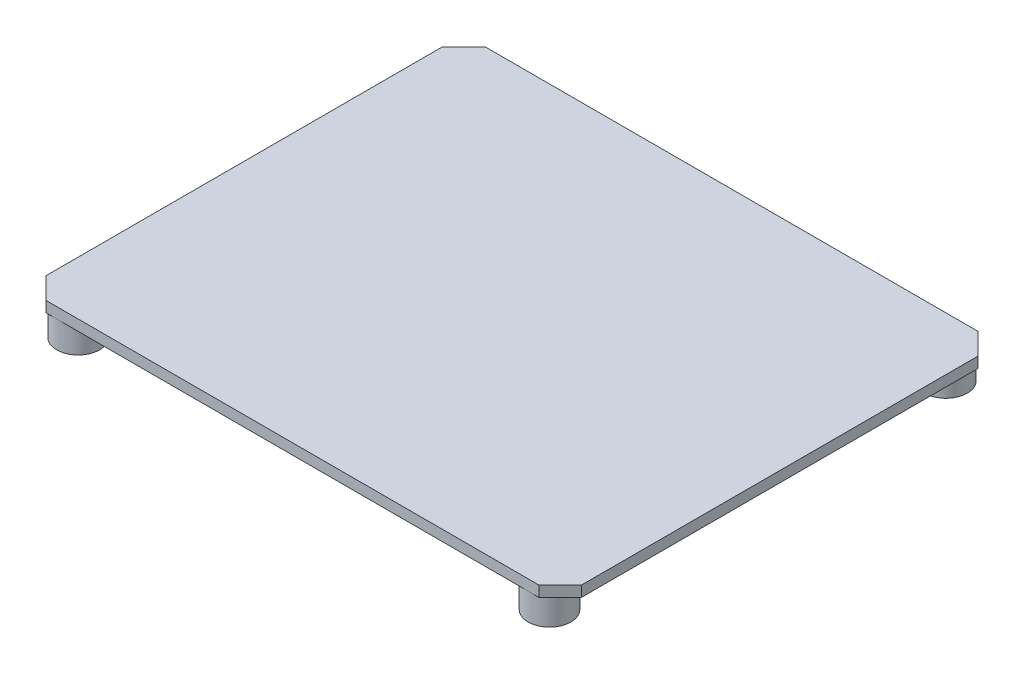
SolidWorks part; units mm, degrees
ref_plane "Front Plane" through (0, 0, 0) normal (0, 0, 1) x (1, 0, 0)
ref_plane "Top Plane" through (0, 0, 0) normal (0, 1, 0) x (1, 0, 0)
ref_plane "Right Plane" through (0, 0, 0) normal (1, 0, 0) x (0, 0, -1)
ref_plane "PZ35_4" through (0, 35.4, 0) normal (0, 1, 0) x (1, 0, 0)
sketch "Sketch1" plane through (0, 35.4, 0) normal (0, 1, 0) x (1, 0, 0)
  line L0 (-46, -102) -> (46, -102)
  line L1 (46, -102) -> (50, -98)
  line L2 (50, -98) -> (50, -24)
  line L3 (50, -24) -> (46, -20)
  line L4 (46, -20) -> (-46, -20)
  line L5 (-46, -20) -> (-50, -24)
  line L6 (-50, -24) -> (-50, -98)
  line L7 (-50, -98) -> (-46, -102)
extrude "Shade Plate" add sketch "Sketch1" along normal blind 2
ref_plane "PZ30_4" through (0, 30.4, 0) normal (0, 1, 0) x (1, 0, 0)
sketch "Sketch2" plane through (0, 30.4, 0) normal (0, 1, 0) x (1, 0, 0)
  circle A0 centre (-44, -24) radius 4
  circle A1 centre (-44, -98) radius 4
  circle A2 centre (44, -24) radius 4
  circle A3 centre (44, -98) radius 4
extrude "Posts" add sketch "Sketch2" along normal blind 5.1
ref_plane "PZ29_9" through (0, 29.9, 0) normal (0, 1, 0) x (1, 0, 0)
sketch "Sketch3" plane through (0, 29.9, 0) normal (0, 1, 0) x (1, 0, 0)
  circle A0 centre (-44, -24) radius 1.25
  circle A1 centre (-44, -98) radius 1.25
  circle A2 centre (44, -24) radius 1.25
  circle A3 centre (44, -98) radius 1.25
extrude "Post Pilots" cut sketch "Sketch3" along normal blind 6.5
equation "\"BOARD_REAR\" = 86.0"
equation "\"BOARD_FRONT\" = 41.0"
equation "\"BOARD_END\" = 22.0"
equation "\"BOARD_ANGLED\" = 30.0"
equation "\"BOARD_DEPTH\" = 41.8431"
equation "\"PCB_T\" = 1.6"
equation "\"ABOVE_PCB\" = 14.0"
equation "\"BELOW_PCB\" = 6.0"
equation "\"MID_PARTS_H\" = 9.0"
equation "\"BOARD_HOLE_PILOT\" = 1.6"
equation "\"J2_X\" = 19.0"
equation "\"DUPONT_DROP\" = 14.0"
equation "\"BEND_R\" = 5.0"
equation "\"BOARD_GAP\" = 3.0"
equation "\"TOF_FOV\" = 25.0"
equation "\"TOF_MARGIN_DEG\" = 5.0"
equation "\"TOF_WIN_MARGIN\" = 1.0"
equation "\"TOF_Z\" = 9.0"
equation "\"TOF_SIDE_BEARING\" = 90.0"
equation "\"TOF_CONE_LEN\" = 70.0"
equation "\"CAM_W\" = 29.2"
equation "\"CAM_H\" = 28.2"
equation "\"CAM_D\" = 12.35"
equation "\"CAM_FRONT_Y\" = 43.0"
equation "\"CAM_BOTTOM_Z\" = 17.0"
equation "\"CAM_LENS_UP\" = 11.6"
equation "\"CAM_LENS_OPEN\" = 9.6"
equation "\"CAM_HFOV\" = 53.5"
equation "\"CAM_VFOV\" = 41.41"
equation "\"CAM_FOV_MARGIN\" = 3.0"
equation "\"CAM_FIT\" = 0.3"
equation "\"RIBBON_W\" = 16.0"
equation "\"RIBBON_T\" = 0.3"
equation "\"RIBBON_LEN\" = 150.0"
equation "\"RIBBON_EXIT_Y\" = 35.0"
equation "\"WALL\" = 2.4"
equation "\"HEAD_X\" = 48.4"
equation "\"HEAD_REAR_Y\" = -11.9"
equation "\"CAM_FOAM\" = 2.8"
equation "\"HEAD_FRONT_Y\" = 48.2"
equation "\"HEAD_TOP_Z\" = 50.6"
equation "\"HEAD_BOT_Z\" = -28.4"
equation "\"HEAD_SPLIT_Z\" = -4.0"
equation "\"SKIRT_T\" = 1.2"
equation "\"SKIRT_H\" = 3.0"
equation "\"SKIRT_FIT\" = 0.3"
equation "\"VISOR\" = 7.8"
equation "\"VISOR_Z\" = 40.0"
equation "\"ROOF_SLOPE_Y\" = 40.0"
equation "\"ROOF_CHAMFER\" = 10.0"
equation "\"REAR_CHAMFER\" = 10.0"
equation "\"CORNER_CHAMFER\" = 6.0"
equation "\"LOWER_SIDE_FACET\" = 6.0"
equation "\"LIGHTBAR_DEPTH\" = 1.0"
equation "\"HOOD_Z\" = 14.0"
equation "\"HOOD_L\" = 6.0"
equation "\"SIDE_HOOD_L\" = 4.0"
equation "\"INSERT_M3_D\" = 4.0"
equation "\"INSERT_M3_L\" = 6.0"
equation "\"M3_CLEAR\" = 3.4"
equation "\"M2_PILOT\" = 1.6"
equation "\"M25_PILOT\" = 2.2"
equation "\"BOX_X\" = 72.4"
equation "\"BOX_FRONT_Y\" = -11.9"
equation "\"BOX_REAR_Y\" = -124.4"
equation "\"BOX_BOT_Z\" = -28.4"
equation "\"BOX_TOP_Z\" = 28.0"
equation "\"LID_T\" = 2.4"
equation "\"LID_SKIRT\" = 1.6"
equation "\"LID_TONGUE_H\" = 3.0"
equation "\"LID_FIT\" = 0.3"
equation "\"PI_STANDOFF\" = 10.0"
equation "\"BOX_REAR_CHAMFER\" = 8.0"
equation "\"BOX_REAR_FACET\" = 4.0"
equation "\"VENT_UPSTAND\" = 3.0"
equation "\"TUBE_D\" = 22.2"
equation "\"TUBE_LINER\" = 1.0"
equation "\"MOUNT_Y\" = -70.0"
equation "\"RAIL_W\" = 30.0"
equation "\"RAIL_W2\" = 38.0"
equation "\"RAIL_H\" = 6.0"
equation "\"SLIDE\" = 0.3"
equation "\"STOP_T\" = 6.0"
equation "\"CLAMP_W\" = 40.0"
equation "\"CLAMP_HALF\" = 20.0"
equation "\"CLAMP_DROP\" = 12.0"
equation "\"CAP_T\" = 12.0"
equation "\"CLAMP_BOLT_OFF\" = 16.6"
equation "\"M5_INSERT_D\" = 6.4"
equation "\"M5_CLEAR\" = 5.5"
equation "\"LOCK_D\" = 3.3"
equation "\"POD_TILT_DEG\" = 0.0"
equation "\"PRINT_LIMIT\" = 180.0"
equation "\"PI5_L\" = 85.0"
equation "\"PI5_W\" = 56.0"
equation "\"PI5_T\" = 1.6"
equation "\"PI5_USBC_BX\" = 11.2"
equation "\"PI5_ETH_BY\" = 10.2"
equation "\"PI5_PORT_OVERHANG\" = 3.0"
equation "\"PI5_FPC_H\" = 5.0"
equation "\"PI5_FPC_USE\" = 0.0"
equation "\"PI5_PIN1_BX\" = 8.37"
equation "\"HEADER_BASE_H\" = 2.5"
equation "\"DUPONT_L\" = 14.0"
equation "\"PI5_UNDERSIDE\" = 1.5"
equation "\"COOLER_H\" = 15.0"
equation "\"HAT_W\" = 65.0"
equation "\"HAT_D\" = 56.5"
equation "\"HAT_T\" = 1.6"
equation "\"HAT_SPACER\" = 16.0"
equation "\"HAILO_H\" = 10.0"
equation "\"STACK_PINS_H\" = 6.0"
equation "\"DUPONT_SEAT\" = 0.5"
equation "\"PCIE_FFC_LOOP\" = 6.0"
equation "\"HAILO_AIR_GAP_MIN\" = 8.0"
equation "\"M25_CLEAR\" = 2.7"
equation "\"PI_X0\" = -55.0"
equation "\"PI_Y1\" = -36.5"
equation "\"PI_Y0\" = -92.5"
equation "\"BOX_LEN\" = 112.5"
equation "\"COVER_T\" = 3.0"
equation "\"COVER_TOP_Z\" = 6.5"
equation "\"SIDE_LEDGE_Z\" = -0.5"
equation "\"UPPER_LEDGE_Z\" = 17.0"
equation "\"REAR_LEDGE_Z\" = 8.0"
equation "\"LEDGE_L\" = 4.0"
equation "\"LEDGE_TIP\" = 1.5"
equation "\"RIBBON_W_PI\" = 11.5"
equation "\"RIBBON_RUN_Z\" = 12.0"
equation "\"RIBBON_SPEC_LEN\" = 200.0"
